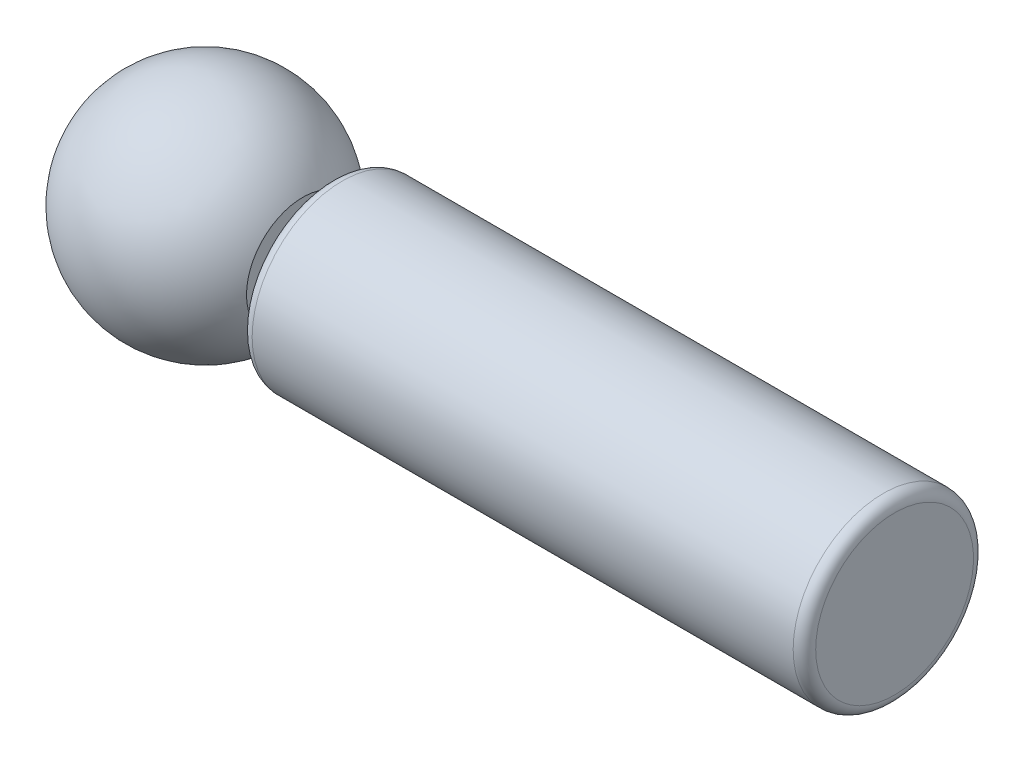
SolidWorks part; units mm, degrees
ref_plane "Front Plane" through (0, 0, 0) normal (0, 0, 1) x (1, 0, 0)
ref_plane "Top Plane" through (0, 0, 0) normal (0, 1, 0) x (1, 0, 0)
ref_plane "Right Plane" through (0, 0, 0) normal (1, 0, 0) x (0, 0, -1)
sketch "Sketch1" plane through (0, 0, 0) normal (0, 1, 0) x (1, 0, 0)
  line L0 (0, 0) -> (61.1603, 0)
  line L1 (61.1603, 0) -> (61.1603, 8)
  line L3 (0, 0) -> (-10, 0)
  line L4 (8.6603, 5) -> (8.6603, 3.5)
  line L5 (10.4103, 2.75) -> (9.4103, 2.75)
  line L6 (11.1603, 3.5) -> (11.1603, 8)
  line L8 (11.1603, 8) -> (61.1603, 8)
  arc A0 (-10, 0) -> (8.6603, 5) centre (0, 0) cw
  arc A5 (11.1603, 3.5) -> (10.4103, 2.75) centre (10.4103, 3.5) cw
  arc A6 (9.4103, 2.75) -> (8.6603, 3.5) centre (9.4103, 3.5) cw
  point P9 (8.5397, 3.522)
  point P11 (0, 0)
  point P13 (0, 0)
  point P16 (0, 0)
  dimension "D1" = 0.75
  dimension "D2" = 10
  dimension "D3" = 0.75
  dimension "D4" = 50
  dimension "D5" = 1.5
  dimension "D6" = 8
  dimension "D7" = 4.5
  dimension "D8" = 1
revolve "Revolve1" add sketch "Sketch1" angle 360 about L0
fillet "Fillet1" radius 1 2 edges at (11.1603, 0, 8) (61.1603, 0, 8)
